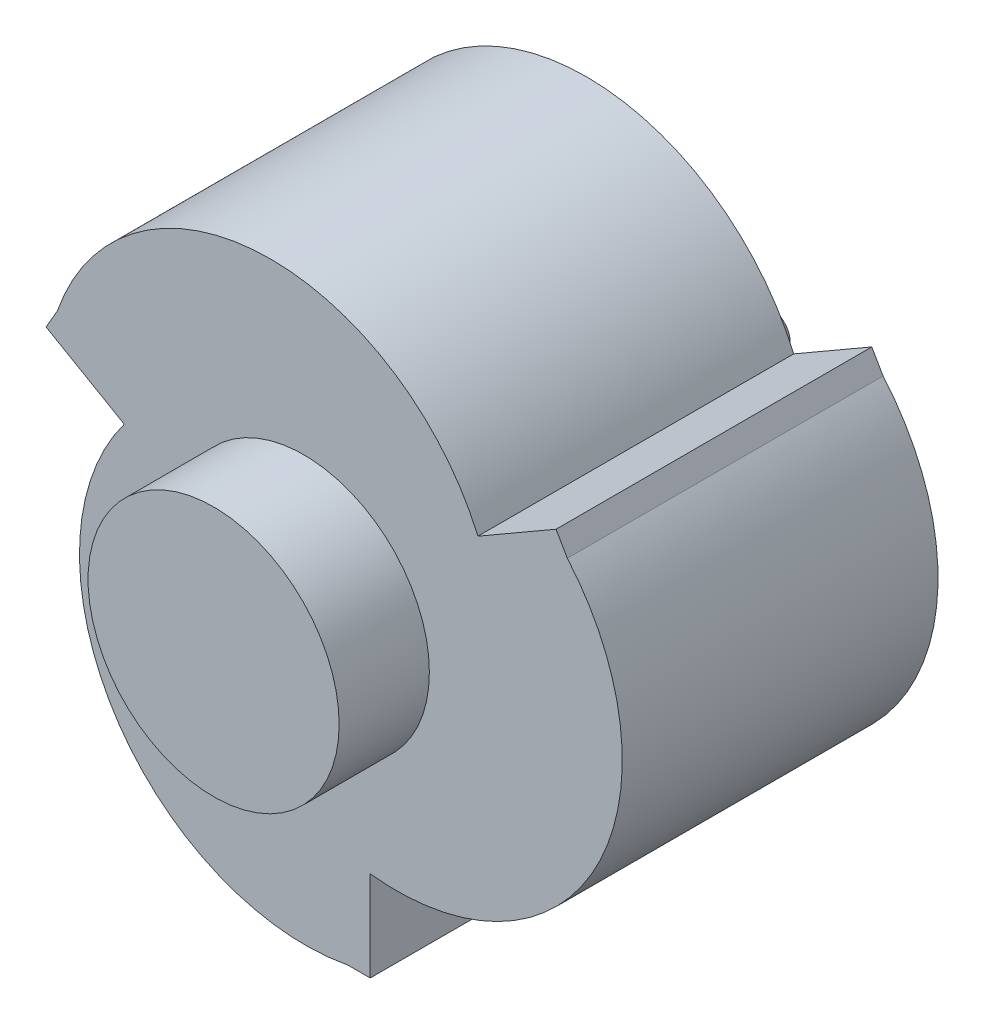
SolidWorks part; units mm, degrees
ref_plane "Alzado" through (0, 0, 0) normal (0, 0, 1) x (1, 0, 0)
ref_plane "Planta" through (0, 0, 0) normal (0, 1, 0) x (1, 0, 0)
ref_plane "Vista lateral" through (0, 0, 0) normal (1, 0, 0) x (0, 0, -1)
sketch "Croquis1" plane through (0, 0, 0) normal (0, 0, 1) x (1, 0, 0)
  line L0 (-53.6678, 33.465) -> (-54.4178, 34.7641)
  line L1 (-54.5075, 31.7452) -> (-55.0163, 32.6264)
  line L2 (-55.0163, 32.6264) -> (-60.2125, 29.6264)
  line L3 (-87.5846, 30.752) -> (-88.3346, 29.453)
  line L4 (-85.6753, 30.8847) -> (-86.184, 30.0035)
  line L5 (-86.184, 30.0035) -> (-80.9879, 27.0035)
  line L6 (-88.3346, 29.453) -> (-83.1384, 26.453)
  line L7 (-54.4178, 34.7641) -> (-59.6139, 31.7641)
  line L8 (-68.2767, 2.7357) -> (-66.7767, 2.7357)
  line L9 (-69.3462, 4.3229) -> (-68.3286, 4.3229)
  line L10 (-68.3286, 4.3229) -> (-68.3286, 10.3229)
  line L11 (-66.7767, 2.7357) -> (-66.7767, 8.7357)
  arc A0 (-80.9879, 27.0035) -> (-69.3462, 4.3229) centre (-70.9053, 17.8507) ccw
  arc A1 (-83.1384, 26.453) -> (-68.2767, 2.7357) centre (-71.0995, 17.4819) ccw
  arc A2 (-60.2125, 29.6264) -> (-85.6753, 30.8847) centre (-73.1803, 25.471) ccw
  arc A3 (-59.6139, 31.7641) -> (-87.5846, 30.752) centre (-73.4026, 25.8236) ccw
  arc A4 (-68.3286, 10.3229) -> (-54.5075, 31.7452) centre (-65.4434, 23.6311) ccw
  arc A5 (-66.7767, 8.7357) -> (-53.6678, 33.465) centre (-65.0269, 23.6473) ccw
  point P16 (-69.6242, 21.6176)
  point P24 (-69.6242, 21.6176)
  point P25 (-69.843, 22.3176)
  point P33 (-69.5543, 21.8176)
  point P49 (-69.843, 22.3176)
  point P50 (-69.843, 22.3176)
  dimension "D6" = 14.9549
  dimension "D8" = 13.6173
  dimension "D3" = 1.5
  dimension "D4" = 6
  dimension "D7" = 6
  dimension "D9" = 0
  dimension "D10" = 90
  dimension "D2" = 3
  dimension "D5" = 3
extrude "Saliente-Extruir1" add sketch "Croquis1" along normal blind 18
sketch "Croquis2" plane through (0, 0, 0) normal (0, 0, -1) x (-1, 0, 0)
  line L0 (87.5846, 30.752) -> (88.3346, 29.453)
  line L1 (88.3346, 29.453) -> (83.1384, 26.453)
  line L2 (66.7767, 2.7357) -> (66.7767, 8.7357)
  line L3 (68.2767, 2.7357) -> (66.7767, 2.7357)
  line L4 (54.4178, 34.7641) -> (59.6139, 31.7641)
  line L5 (53.6678, 33.465) -> (54.4178, 34.7641)
  arc A1 (83.1384, 26.453) -> (68.2767, 2.7357) centre (71.0995, 17.4819) cw
  arc A2 (66.7767, 8.7357) -> (53.6678, 33.465) centre (65.0269, 23.6473) cw
  arc A3 (59.6139, 31.7641) -> (87.5846, 30.752) centre (73.4026, 25.8236) cw
  circle A4 centre (69.843, 22.3176) radius 2.7
  point P24 (69.843, 22.3176)
extrude "Saliente-Extruir2" add sketch "Croquis2" along normal blind 1.5
sketch "Croquis3" plane through (0, 0, 18) normal (0, 0, 1) x (1, 0, 0)
  line L0 (-66.7767, 8.7357) -> (-66.7767, 2.7357)
  line L1 (-66.7767, 2.7357) -> (-68.2767, 2.7357)
  line L2 (-83.1384, 26.453) -> (-88.3346, 29.453)
  line L3 (-88.3346, 29.453) -> (-87.5846, 30.752)
  line L4 (-59.6139, 31.7641) -> (-54.4178, 34.7641)
  line L5 (-54.4178, 34.7641) -> (-53.6678, 33.465)
  arc A0 (-68.2767, 2.7357) -> (-83.1384, 26.453) centre (-71.0995, 17.4819) cw
  arc A2 (-87.5846, 30.752) -> (-59.6139, 31.7641) centre (-73.4026, 25.8236) cw
  arc A3 (-53.6678, 33.465) -> (-66.7767, 8.7357) centre (-65.0269, 23.6473) cw
  point P23 (-69.843, 22.3176)
extrude "Saliente-Extruir3" add sketch "Croquis3" along normal blind 1.5
sketch "Croquis6" plane through (0, 0, -1.5) normal (0, 0, -1) x (-1, 0, 0)
  line L1 (72.543, 22.3176) -> (67.143, 22.3176)
  line L2 (72.543, 22.3176) -> (72.543, 20.5138)
  line L3 (72.543, 20.5138) -> (67.143, 20.5138)
  line L4 (67.143, 22.3176) -> (67.143, 20.5138)
  circle A1 centre (69.843, 22.3176) radius 2.7 construction
extrude "Saliente-Extruir7" add sketch "Croquis6" along normal blind 10
ref_plane "Plano1" through (0, 22.3176, 0) normal (0, 1, 0) x (1, 0, 0)
sketch "Croquis10" plane through (0, 22.3176, 0) normal (0, 1, 0) x (1, 0, 0)
  line L1 (-72.543, 1.5) -> (-67.143, 1.5)
  line L2 (-72.543, 1.5) -> (-72.543, 11.5)
  line L3 (-72.543, 11.5) -> (-67.143, 11.5)
  line L4 (-67.143, 1.5) -> (-67.143, 11.5)
extrude "Cortar-Extruir3" cut sketch "Croquis10" against normal blind 10
sketch "Croquis11" plane through (0, 22.3176, 0) normal (0, 1, 0) x (1, 0, 0)
  line L0 (-72.543, 1.5) -> (-79.543, 1.5)
  line L1 (-72.543, 1.5) -> (-72.543, 11.5)
  line L2 (-72.543, 11.5) -> (-79.543, 1.5)
  line L5 (-71.193, -19.5) -> (-79.543, -19.5)
  line L6 (-79.543, -19.5) -> (-79.543, -25.5)
  line L7 (-79.543, -25.5) -> (-71.193, -25.5)
  line L8 (-71.193, -25.5) -> (-71.193, -19.5)
revolve "Revolución1" add sketch "Croquis11" angle 360 about L8
